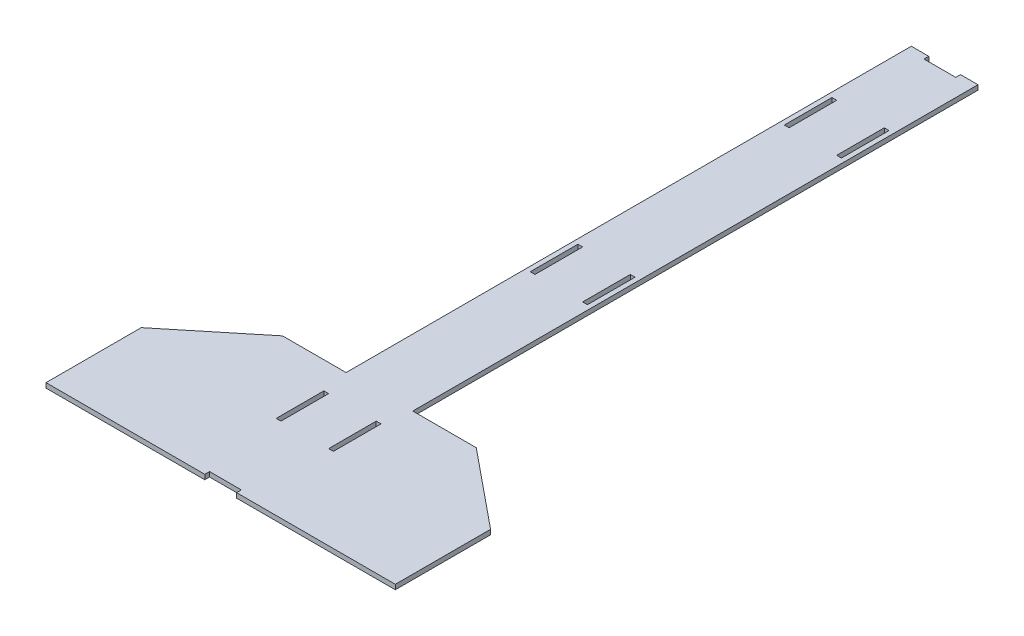
SolidWorks part; units mm, degrees
material "ABS"
ref_plane "Front Plane" through (0, 0, 0) normal (0, 0, 1) x (1, 0, 0)
ref_plane "Top Plane" through (0, 0, 0) normal (0, 1, 0) x (1, 0, 0)
ref_plane "Right Plane" through (0, 0, 0) normal (1, 0, 0) x (0, 0, -1)
sketch "Sketch1" plane through (0, 0, 0) normal (0, 1, 0) x (1, 0, 0)
  line L0 (31, 456) -> (42, 456)
  line L2 (0, 100) -> (0, 456)
  line L3 (0, 456) -> (11, 456)
  line L4 (42, 100) -> (42, 456)
  line L6 (11, 0) -> (11, 3)
  line L7 (11, 3) -> (31, 3)
  line L8 (31, 0) -> (31, 3)
  line L10 (11, 456) -> (11, 453)
  line L11 (11, 453) -> (31, 453)
  line L12 (31, 456) -> (31, 453)
  line L13 (31, 0) -> (131, 0)
  line L15 (36, 83) -> (39, 83)
  line L16 (36, 83) -> (36, 53)
  line L17 (36, 53) -> (39, 53)
  line L18 (39, 83) -> (39, 53)
  line L19 (36, 243) -> (39, 243)
  line L20 (36, 243) -> (36, 213)
  line L21 (36, 213) -> (39, 213)
  line L22 (39, 243) -> (39, 213)
  line L23 (36, 403) -> (39, 403)
  line L24 (36, 403) -> (36, 373)
  line L25 (36, 373) -> (39, 373)
  line L26 (39, 403) -> (39, 373)
  line L30 (21, 3) -> (21, 43.5772) construction
  line L35 (6, 53) -> (3, 53)
  line L36 (6, 83) -> (3, 83)
  line L37 (3, 83) -> (3, 53)
  line L38 (6, 83) -> (6, 53)
  line L39 (6, 213) -> (3, 213)
  line L40 (6, 243) -> (6, 213)
  line L41 (3, 243) -> (3, 213)
  line L42 (6, 243) -> (3, 243)
  line L43 (6, 373) -> (3, 373)
  line L44 (3, 403) -> (3, 373)
  line L45 (6, 403) -> (3, 403)
  line L46 (6, 403) -> (6, 373)
  line L47 (42, 100) -> (82, 100)
  line L48 (82, 100) -> (131, 60)
  line L49 (131, 60) -> (131, 0)
  line L50 (11, 0) -> (-89, 0)
  line L51 (-89, 60) -> (-89, 0)
  line L52 (-40, 100) -> (-89, 60)
  line L53 (0, 100) -> (-40, 100)
  dimension "D2" = 42
  dimension "D3" = 20
  dimension "D4" = 3
  dimension "D5" = 11
  dimension "D6" = 20
  dimension "D7" = 3
  dimension "D8" = 100
  dimension "D9" = 3
  dimension "D10" = 3
  dimension "D11" = 30
  dimension "D12" = 53
  dimension "D13" = 3
  dimension "D14" = 30
  dimension "D15" = 3
  dimension "D16" = 130
  dimension "D17" = 3
  dimension "D18" = 30
  dimension "D19" = 3
  dimension "D20" = 160
  dimension "D21" = 100
  dimension "D22" = 60
  dimension "D23" = 40
  dimension "D24" = 456
extrude "Boss-Extrude1" add sketch "Sketch1" along normal blind 3
